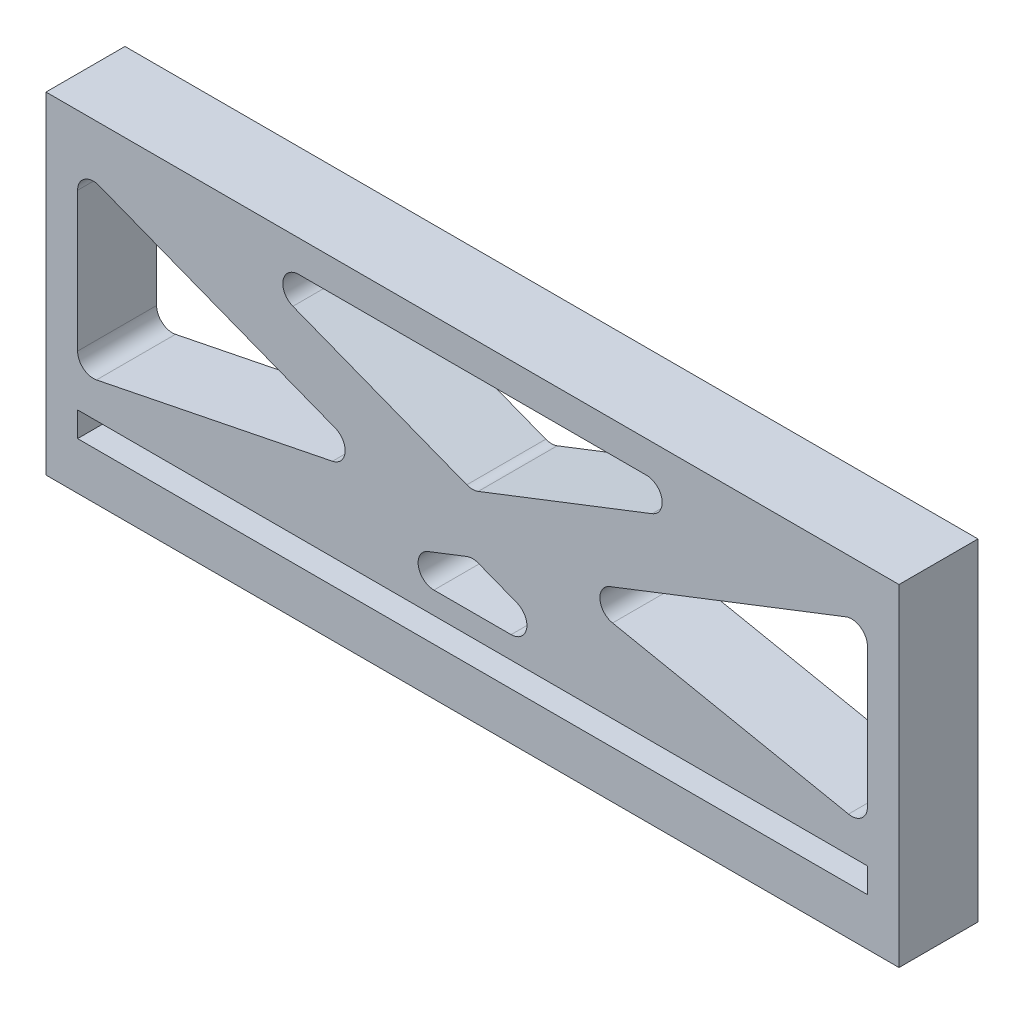
SolidWorks part; units mm, degrees
ref_plane "Front Plane" through (0, 0, 0) normal (0, 0, 1) x (1, 0, 0)
ref_plane "Top Plane" through (0, 0, 0) normal (0, 1, 0) x (1, 0, 0)
ref_plane "Right Plane" through (0, 0, 0) normal (1, 0, 0) x (0, 0, -1)
sketch "Sketch1" plane through (0, 0, 0) normal (0, 0, 1) x (1, 0, 0)
  line L0 (-20.7506, 10.795) -> (0, 2.7253)
  line L1 (-34.29, -13.335) -> (34.29, -13.335)
  line L2 (-34.29, -13.335) -> (-34.29, 13.335)
  line L3 (-34.29, 13.335) -> (34.29, 13.335)
  line L4 (34.29, -13.335) -> (34.29, 13.335)
  line L5 (-34.29, -13.335) -> (34.29, 13.335) construction
  line L6 (-34.29, 13.335) -> (34.29, -13.335) construction
  line L7 (-31.75, -9.525) -> (31.75, -9.525)
  line L8 (-31.75, -9.525) -> (-31.75, -7.525)
  line L9 (-31.75, -7.525) -> (31.75, -7.525)
  line L10 (31.75, -9.525) -> (31.75, -7.525)
  line L11 (-31.75, -9.525) -> (31.75, -7.525) construction
  line L12 (-31.75, -7.525) -> (31.75, -9.525) construction
  line L13 (0, 2.7253) -> (20.7506, 10.795)
  line L14 (20.7506, 10.795) -> (-20.7506, 10.795)
  line L15 (0, 0) -> (0, 2.7253) construction
  line L16 (-10.3753, 6.7602) -> (-11.2959, 4.3929) construction
  line L17 (10.3753, 6.7602) -> (11.2959, 4.3929) construction
  line L18 (0, 10.795) -> (0, 13.335) construction
  line L19 (-31.75, 9.6219) -> (-31.75, -4.985)
  line L20 (-31.75, -4.985) -> (-7.0079, 0)
  line L21 (-7.0079, 0) -> (-31.75, 9.6219)
  line L22 (7.0079, 0) -> (-7.0079, 0) construction
  line L23 (-19.379, 4.811) -> (-18.4584, 7.1782) construction
  line L24 (7.0079, 0) -> (31.75, 9.6219)
  line L25 (31.75, 9.6219) -> (31.75, -4.985)
  line L26 (31.75, -4.985) -> (7.0079, 0)
  line L27 (0, -1.9077) -> (-9.8724, -5.747)
  line L28 (-9.8724, -5.747) -> (9.8724, -5.747)
  line L29 (9.8724, -5.747) -> (0, -1.9077)
  line L30 (0, -1.9077) -> (0, 0) construction
  line L31 (-4.9362, -3.8274) -> (-5.5807, -2.1703) construction
  line L32 (4.9362, -3.8274) -> (5.5807, -2.1703) construction
  line L33 (0, -5.747) -> (0, -7.525) construction
  point P0 (0, 0)
  point P6 (0, -8.525)
  point P27 (0, 0)
  dimension "D1" = 3.81
  dimension "D2" = 2.54
  dimension "D3" = 68.58
  dimension "D4" = 26.67
  dimension "D5" = 2
  dimension "D6" = 2.54
  dimension "D7" = 2.54
  dimension "D8" = 2.54
  dimension "D9" = 1.778
extrude "Boss-Extrude1" add sketch "Sketch1" along normal blind 6.35
fillet "Fillet1" radius 1.27 12 edges at (31.75, 9.6219, 3.175) (31.75, -4.985, 3.175) (7.0079, 0, 3.175) (20.7506, 10.795, 3.175) (-20.7506, 10.795, 3.175) (0, 2.7253, 3.175) (-7.0079, 0, 3.175) (-31.75, 9.6219, 3.175) (-31.75, -4.985, 3.175) (9.8724, -5.747, 3.175) (0, -1.9077, 3.175) (-9.8724, -5.747, 3.175)
